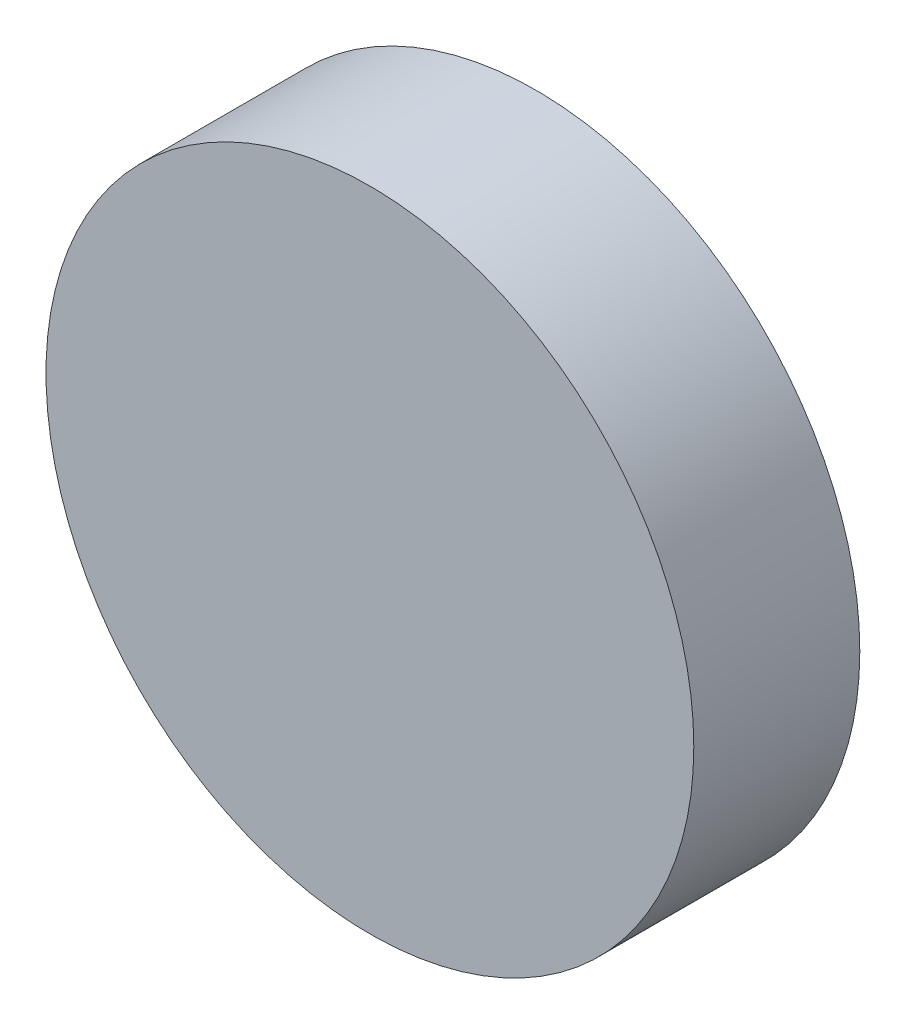
SolidWorks part; units mm, degrees
ref_plane "Front Plane" through (0, 0, 0) normal (0, 0, 1) x (1, 0, 0)
ref_plane "Top Plane" through (0, 0, 0) normal (0, 1, 0) x (1, 0, 0)
ref_plane "Right Plane" through (0, 0, 0) normal (1, 0, 0) x (0, 0, -1)
sketch "Sketch1" plane through (0, 0, 0) normal (0, 0, 1) x (1, 0, 0)
  circle A0 centre (0, 0) radius 27.9
  dimension "D1" = 55.8
extrude "Boss-Extrude1" add sketch "Sketch1" along normal blind 14.3
